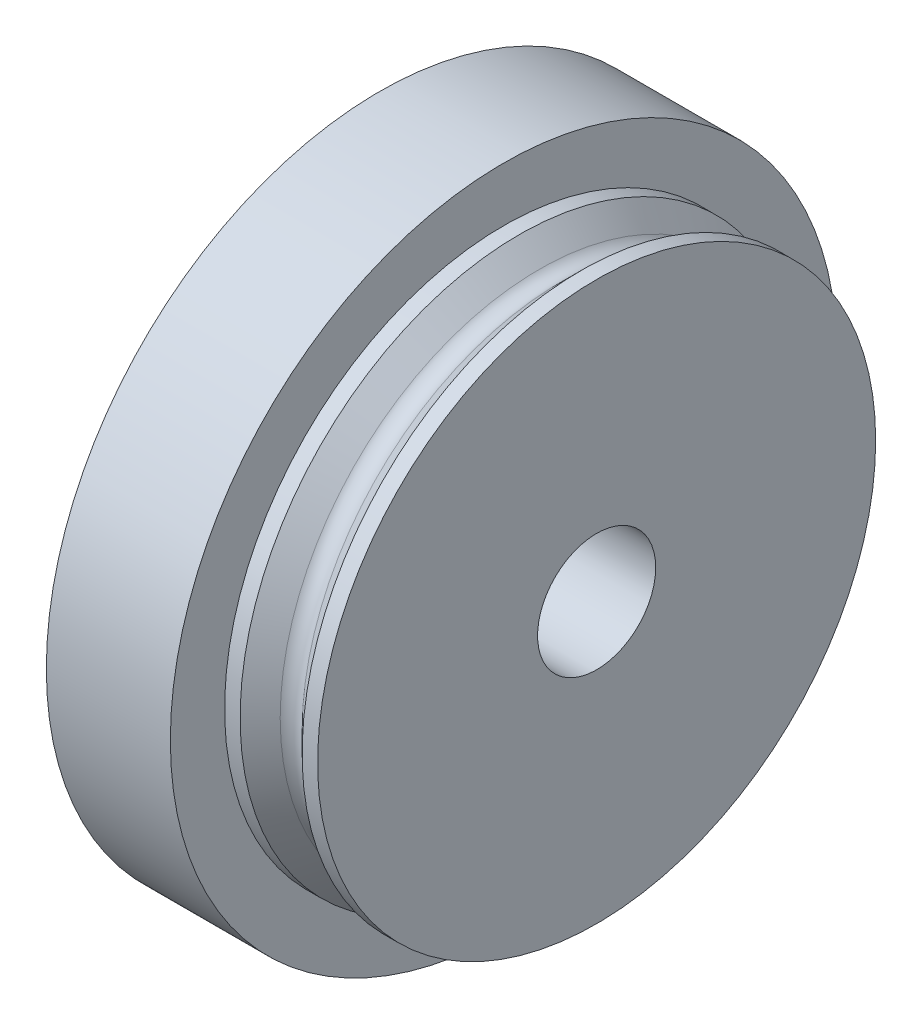
SolidWorks part; units mm, degrees
ref_plane "Front Plane" through (0, 0, 0) normal (0, 0, 1) x (1, 0, 0)
ref_plane "Top Plane" through (0, 0, 0) normal (0, 1, 0) x (1, 0, 0)
ref_plane "Right Plane" through (0, 0, 0) normal (1, 0, 0) x (0, 0, -1)
sketch "Sketch1" plane through (0, 0, 0) normal (0, 0, 1) x (1, 0, 0)
  line L0 (0, 3.81) -> (-14, 3.81)
  line L1 (-14, 3.81) -> (-14, 7.81)
  line L2 (-14, 7.81) -> (-6, 7.81)
  line L3 (-6, 7.81) -> (-6, 18)
  line L4 (-6, 18) -> (0, 18)
  line L5 (0, 18) -> (0, 3.81)
  line L6 (0, 0) -> (-24.6346, 0) construction
  dimension "D1" = 3.81
  dimension "D2" = 18
  dimension "D3" = 6
  dimension "D4" = 8
  dimension "D5" = 4
revolve "Revolve1" add sketch "Sketch1" angle 360 about L6
sketch "Sketch2" plane through (0, 0, 0) normal (0, 1, 0) x (1, 0, 0)
  line L0 (-5, 18) -> (-3.7071, 16.7071)
  line L1 (0, 18) -> (-6, 18) construction
  line L2 (-2.2929, 16.7071) -> (-1, 18)
  line L3 (-5, 18) -> (-1, 18)
  line L4 (0, 0) -> (-6, 0) construction
  line L5 (-6, 18) -> (-6, -18) construction
  arc A0 (-3.7071, 16.7071) -> (-2.2929, 16.7071) centre (-3, 17.4142) ccw
  point P12 (-3, 0)
  point P13 (0, 0)
  point P14 (-3.8159, 16.8159)
  dimension "D1" = 4
  dimension "D3" = 1
  dimension "D2" = 45
revolve "Cut-Revolve1" cut sketch "Sketch2" angle 360 about L4
sketch "Sketch3" plane through (-6, 0, 0) normal (-1, 0, 0) x (0, 0, 1)
  circle A0 centre (0, 0) radius 7.81
  circle A1 centre (0, 0) radius 21.5
  dimension "D1" = 43
extrude "Boss-Extrude1" add sketch "Sketch3" along normal blind 8 separate body
